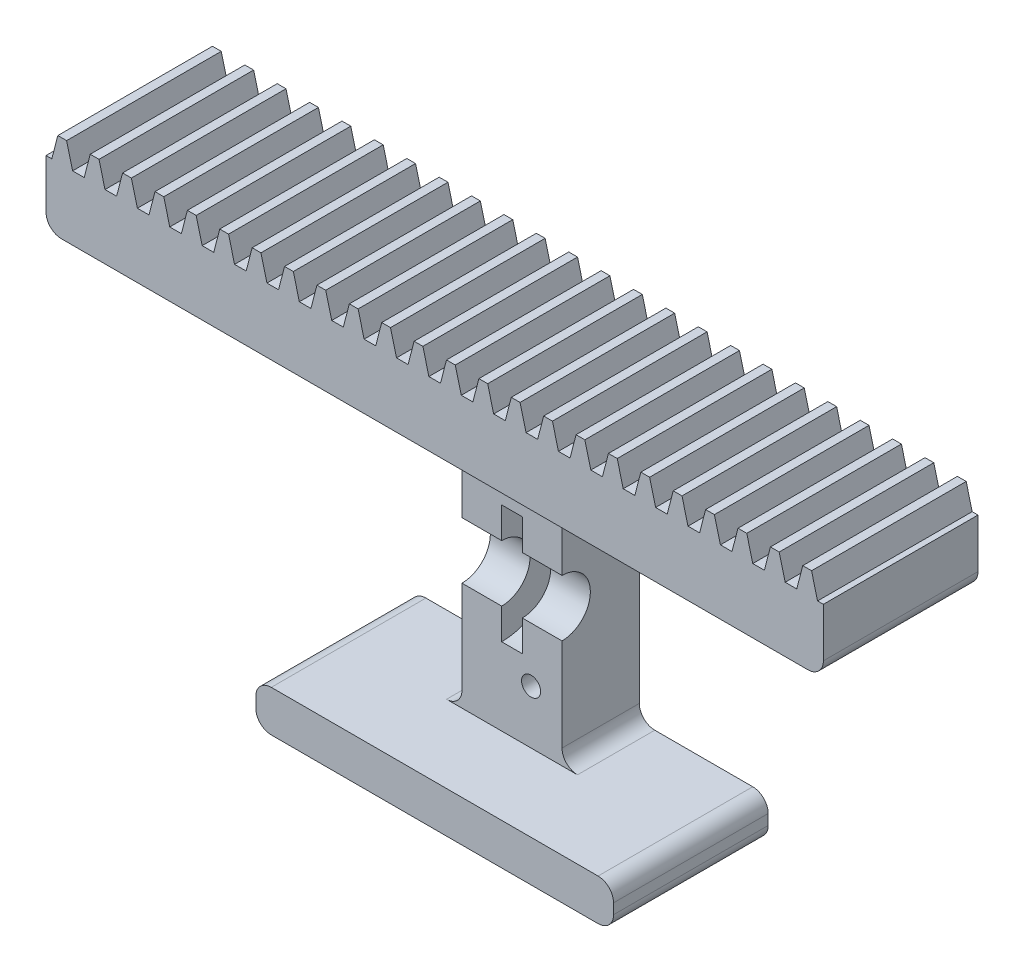
SolidWorks part; units mm, degrees
ref_plane "Plano frontal" through (0, 0, 0) normal (0, 0, 1) x (1, 0, 0)
ref_plane "Plano superior" through (0, 0, 0) normal (0, 1, 0) x (1, 0, 0)
ref_plane "Plano direito" through (0, 0, 0) normal (1, 0, 0) x (0, 0, -1)
sketch "Esboço1" plane through (0, 0, 0) normal (0, 0, 1) x (1, 0, 0)
  line L101 (-148.5074, 17) -> (-149.6712, 12.5)
  line L102 (-149.6712, 12.5) -> (-150.8, 12.5)
  line L103 (-150.8, 12.5) -> (-150.8, 0)
  line L104 (-150.8, 0) -> (0, 0)
  line L105 (0, 0) -> (0, 12.5)
  line L106 (0, 12.5) -> (-1.1253, 12.5)
  line L107 (-1.1253, 12.5) -> (-2.289, 17)
  line L108 (-2.289, 17) -> (-3.9942, 17)
  line L109 (-3.9942, 17) -> (-5.1579, 12.5)
  line L110 (-5.1579, 12.5) -> (-7.4084, 12.5)
  line L111 (-7.4084, 12.5) -> (-8.5722, 17)
  line L112 (-8.5722, 17) -> (-10.2773, 17)
  line L113 (-10.2773, 17) -> (-11.4411, 12.5)
  line L114 (-11.4411, 12.5) -> (-13.6916, 12.5)
  line L115 (-13.6916, 12.5) -> (-14.8554, 17)
  line L116 (-14.8554, 17) -> (-16.5605, 17)
  line L117 (-16.5605, 17) -> (-17.7243, 12.5)
  line L118 (-17.7243, 12.5) -> (-19.9748, 12.5)
  line L119 (-19.9748, 12.5) -> (-21.1386, 17)
  line L120 (-21.1386, 17) -> (-22.8437, 17)
  line L121 (-22.8437, 17) -> (-24.0075, 12.5)
  line L122 (-24.0075, 12.5) -> (-26.258, 12.5)
  line L123 (-26.258, 12.5) -> (-27.4218, 17)
  line L124 (-27.4218, 17) -> (-29.1269, 17)
  line L125 (-29.1269, 17) -> (-30.2907, 12.5)
  line L126 (-30.2907, 12.5) -> (-32.5412, 12.5)
  line L127 (-32.5412, 12.5) -> (-33.705, 17)
  line L128 (-33.705, 17) -> (-35.4101, 17)
  line L129 (-35.4101, 17) -> (-36.5739, 12.5)
  line L130 (-36.5739, 12.5) -> (-38.8244, 12.5)
  line L131 (-38.8244, 12.5) -> (-39.9881, 17)
  line L132 (-39.9881, 17) -> (-41.6933, 17)
  line L133 (-41.6933, 17) -> (-42.857, 12.5)
  line L134 (-42.857, 12.5) -> (-45.1075, 12.5)
  line L135 (-45.1075, 12.5) -> (-46.2713, 17)
  line L136 (-46.2713, 17) -> (-47.9765, 17)
  line L137 (-47.9765, 17) -> (-49.1402, 12.5)
  line L138 (-49.1402, 12.5) -> (-51.3907, 12.5)
  line L139 (-51.3907, 12.5) -> (-52.5545, 17)
  line L140 (-52.5545, 17) -> (-54.2596, 17)
  line L141 (-54.2596, 17) -> (-55.4234, 12.5)
  line L142 (-55.4234, 12.5) -> (-57.6739, 12.5)
  line L143 (-57.6739, 12.5) -> (-58.8377, 17)
  line L144 (-58.8377, 17) -> (-60.5428, 17)
  line L145 (-60.5428, 17) -> (-61.7066, 12.5)
  line L146 (-61.7066, 12.5) -> (-63.9571, 12.5)
  line L147 (-63.9571, 12.5) -> (-65.1209, 17)
  line L148 (-65.1209, 17) -> (-66.826, 17)
  line L149 (-66.826, 17) -> (-67.9898, 12.5)
  line L150 (-67.9898, 12.5) -> (-70.2403, 12.5)
  line L151 (-70.2403, 12.5) -> (-71.4041, 17)
  line L152 (-71.4041, 17) -> (-73.1092, 17)
  line L153 (-73.1092, 17) -> (-74.273, 12.5)
  line L154 (-74.273, 12.5) -> (-76.5235, 12.5)
  line L155 (-76.5235, 12.5) -> (-77.6873, 17)
  line L156 (-77.6873, 17) -> (-79.3924, 17)
  line L157 (-79.3924, 17) -> (-80.5562, 12.5)
  line L158 (-80.5562, 12.5) -> (-82.8067, 12.5)
  line L159 (-82.8067, 12.5) -> (-83.9704, 17)
  line L160 (-83.9704, 17) -> (-85.6756, 17)
  line L161 (-85.6756, 17) -> (-86.8393, 12.5)
  line L162 (-86.8393, 12.5) -> (-89.0898, 12.5)
  line L163 (-89.0898, 12.5) -> (-90.2536, 17)
  line L164 (-90.2536, 17) -> (-91.9587, 17)
  line L165 (-91.9587, 17) -> (-93.1225, 12.5)
  line L166 (-93.1225, 12.5) -> (-95.373, 12.5)
  line L167 (-95.373, 12.5) -> (-96.5368, 17)
  line L168 (-96.5368, 17) -> (-98.2419, 17)
  line L169 (-98.2419, 17) -> (-99.4057, 12.5)
  line L170 (-99.4057, 12.5) -> (-101.6562, 12.5)
  line L171 (-101.6562, 12.5) -> (-102.82, 17)
  line L172 (-102.82, 17) -> (-104.5251, 17)
  line L173 (-104.5251, 17) -> (-105.6889, 12.5)
  line L174 (-105.6889, 12.5) -> (-107.9394, 12.5)
  line L175 (-107.9394, 12.5) -> (-109.1032, 17)
  line L176 (-109.1032, 17) -> (-110.8083, 17)
  line L177 (-110.8083, 17) -> (-111.9721, 12.5)
  line L178 (-111.9721, 12.5) -> (-114.2226, 12.5)
  line L179 (-114.2226, 12.5) -> (-115.3864, 17)
  line L180 (-115.3864, 17) -> (-117.0915, 17)
  line L181 (-117.0915, 17) -> (-118.2553, 12.5)
  line L182 (-118.2553, 12.5) -> (-120.5058, 12.5)
  line L183 (-120.5058, 12.5) -> (-121.6696, 17)
  line L184 (-121.6696, 17) -> (-123.3747, 17)
  line L185 (-123.3747, 17) -> (-124.5385, 12.5)
  line L186 (-124.5385, 12.5) -> (-126.789, 12.5)
  line L187 (-126.789, 12.5) -> (-127.9527, 17)
  line L188 (-127.9527, 17) -> (-129.6579, 17)
  line L189 (-129.6579, 17) -> (-130.8216, 12.5)
  line L190 (-130.8216, 12.5) -> (-133.0721, 12.5)
  line L191 (-133.0721, 12.5) -> (-134.2359, 17)
  line L192 (-134.2359, 17) -> (-135.941, 17)
  line L193 (-135.941, 17) -> (-137.1048, 12.5)
  line L194 (-137.1048, 12.5) -> (-139.3553, 12.5)
  line L195 (-139.3553, 12.5) -> (-140.5191, 17)
  line L196 (-140.5191, 17) -> (-142.2242, 17)
  line L197 (-142.2242, 17) -> (-143.388, 12.5)
  line L198 (-143.388, 12.5) -> (-145.6385, 12.5)
  line L199 (-145.6385, 12.5) -> (-146.8023, 17)
  line L200 (-146.8023, 17) -> (-148.5074, 17)
  line L201 (-148.5074, 17) -> (-149.6712, 12.5)
  line L202 (-149.6712, 12.5) -> (-150.8, 12.5)
  line L203 (-150.8, 12.5) -> (-150.8, 0)
  line L204 (-150.8, 0) -> (0, 0)
  line L205 (0, 0) -> (0, 12.5)
  line L206 (0, 12.5) -> (-1.1253, 12.5)
  line L207 (-1.1253, 12.5) -> (-2.289, 17)
  line L208 (-2.289, 17) -> (-3.9942, 17)
  line L209 (-3.9942, 17) -> (-5.1579, 12.5)
  line L210 (-5.1579, 12.5) -> (-7.4084, 12.5)
  line L211 (-7.4084, 12.5) -> (-8.5722, 17)
  line L212 (-8.5722, 17) -> (-10.2773, 17)
  line L213 (-10.2773, 17) -> (-11.4411, 12.5)
  line L214 (-11.4411, 12.5) -> (-13.6916, 12.5)
  line L215 (-13.6916, 12.5) -> (-14.8554, 17)
  line L216 (-14.8554, 17) -> (-16.5605, 17)
  line L217 (-16.5605, 17) -> (-17.7243, 12.5)
  line L218 (-17.7243, 12.5) -> (-19.9748, 12.5)
  line L219 (-19.9748, 12.5) -> (-21.1386, 17)
  line L220 (-21.1386, 17) -> (-22.8437, 17)
  line L221 (-22.8437, 17) -> (-24.0075, 12.5)
  line L222 (-24.0075, 12.5) -> (-26.258, 12.5)
  line L223 (-26.258, 12.5) -> (-27.4218, 17)
  line L224 (-27.4218, 17) -> (-29.1269, 17)
  line L225 (-29.1269, 17) -> (-30.2907, 12.5)
  line L226 (-30.2907, 12.5) -> (-32.5412, 12.5)
  line L227 (-32.5412, 12.5) -> (-33.705, 17)
  line L228 (-33.705, 17) -> (-35.4101, 17)
  line L229 (-35.4101, 17) -> (-36.5739, 12.5)
  line L230 (-36.5739, 12.5) -> (-38.8244, 12.5)
  line L231 (-38.8244, 12.5) -> (-39.9881, 17)
  line L232 (-39.9881, 17) -> (-41.6933, 17)
  line L233 (-41.6933, 17) -> (-42.857, 12.5)
  line L234 (-42.857, 12.5) -> (-45.1075, 12.5)
  line L235 (-45.1075, 12.5) -> (-46.2713, 17)
  line L236 (-46.2713, 17) -> (-47.9765, 17)
  line L237 (-47.9765, 17) -> (-49.1402, 12.5)
  line L238 (-49.1402, 12.5) -> (-51.3907, 12.5)
  line L239 (-51.3907, 12.5) -> (-52.5545, 17)
  line L240 (-52.5545, 17) -> (-54.2596, 17)
  line L241 (-54.2596, 17) -> (-55.4234, 12.5)
  line L242 (-55.4234, 12.5) -> (-57.6739, 12.5)
  line L243 (-57.6739, 12.5) -> (-58.8377, 17)
  line L244 (-58.8377, 17) -> (-60.5428, 17)
  line L245 (-60.5428, 17) -> (-61.7066, 12.5)
  line L246 (-61.7066, 12.5) -> (-63.9571, 12.5)
  line L247 (-63.9571, 12.5) -> (-65.1209, 17)
  line L248 (-65.1209, 17) -> (-66.826, 17)
  line L249 (-66.826, 17) -> (-67.9898, 12.5)
  line L250 (-67.9898, 12.5) -> (-70.2403, 12.5)
  line L251 (-70.2403, 12.5) -> (-71.4041, 17)
  line L252 (-71.4041, 17) -> (-73.1092, 17)
  line L253 (-73.1092, 17) -> (-74.273, 12.5)
  line L254 (-74.273, 12.5) -> (-76.5235, 12.5)
  line L255 (-76.5235, 12.5) -> (-77.6873, 17)
  line L256 (-77.6873, 17) -> (-79.3924, 17)
  line L257 (-79.3924, 17) -> (-80.5562, 12.5)
  line L258 (-80.5562, 12.5) -> (-82.8067, 12.5)
  line L259 (-82.8067, 12.5) -> (-83.9704, 17)
  line L260 (-83.9704, 17) -> (-85.6756, 17)
  line L261 (-85.6756, 17) -> (-86.8393, 12.5)
  line L262 (-86.8393, 12.5) -> (-89.0898, 12.5)
  line L263 (-89.0898, 12.5) -> (-90.2536, 17)
  line L264 (-90.2536, 17) -> (-91.9587, 17)
  line L265 (-91.9587, 17) -> (-93.1225, 12.5)
  line L266 (-93.1225, 12.5) -> (-95.373, 12.5)
  line L267 (-95.373, 12.5) -> (-96.5368, 17)
  line L268 (-96.5368, 17) -> (-98.2419, 17)
  line L269 (-98.2419, 17) -> (-99.4057, 12.5)
  line L270 (-99.4057, 12.5) -> (-101.6562, 12.5)
  line L271 (-101.6562, 12.5) -> (-102.82, 17)
  line L272 (-102.82, 17) -> (-104.5251, 17)
  line L273 (-104.5251, 17) -> (-105.6889, 12.5)
  line L274 (-105.6889, 12.5) -> (-107.9394, 12.5)
  line L275 (-107.9394, 12.5) -> (-109.1032, 17)
  line L276 (-109.1032, 17) -> (-110.8083, 17)
  line L277 (-110.8083, 17) -> (-111.9721, 12.5)
  line L278 (-111.9721, 12.5) -> (-114.2226, 12.5)
  line L279 (-114.2226, 12.5) -> (-115.3864, 17)
  line L280 (-115.3864, 17) -> (-117.0915, 17)
  line L281 (-117.0915, 17) -> (-118.2553, 12.5)
  line L282 (-118.2553, 12.5) -> (-120.5058, 12.5)
  line L283 (-120.5058, 12.5) -> (-121.6696, 17)
  line L284 (-121.6696, 17) -> (-123.3747, 17)
  line L285 (-123.3747, 17) -> (-124.5385, 12.5)
  line L286 (-124.5385, 12.5) -> (-126.789, 12.5)
  line L287 (-126.789, 12.5) -> (-127.9527, 17)
  line L288 (-127.9527, 17) -> (-129.6579, 17)
  line L289 (-129.6579, 17) -> (-130.8216, 12.5)
  line L290 (-130.8216, 12.5) -> (-133.0721, 12.5)
  line L291 (-133.0721, 12.5) -> (-134.2359, 17)
  line L292 (-134.2359, 17) -> (-135.941, 17)
  line L293 (-135.941, 17) -> (-137.1048, 12.5)
  line L294 (-137.1048, 12.5) -> (-139.3553, 12.5)
  line L295 (-139.3553, 12.5) -> (-140.5191, 17)
  line L296 (-140.5191, 17) -> (-142.2242, 17)
  line L297 (-142.2242, 17) -> (-143.388, 12.5)
  line L298 (-143.388, 12.5) -> (-145.6385, 12.5)
  line L299 (-145.6385, 12.5) -> (-146.8023, 17)
  line L300 (-146.8023, 17) -> (-148.5074, 17)
  dimension "D1" = 0
extrude "Ressalto-extrusão1" add sketch "Esboço1" against normal up to surface (30 mm away)
sketch "Esboço2" plane through (0, 0, -30) normal (0, 0, -1) x (-1, 0, 0)
  line L0 (0, 0) -> (150.8, 0) construction
  line L1 (85.1, 0) -> (65.7, 0)
  line L2 (85.1, 0) -> (85.1, -55)
  line L4 (65.7, 0) -> (65.7, -55)
  line L6 (85.1, -55) -> (110.1, -55)
  line L7 (110.1, -55) -> (110.1, -63)
  line L8 (77.1, -39.9) -> (77.1, -18.1) construction
  line L9 (73.7, -18.1) -> (73.7, -39.9) construction
  line L10 (65.7, -55) -> (40.7, -55)
  line L11 (40.7, -55) -> (40.7, -63)
  line L14 (150.8, 0) -> (0, 0) construction
  line L15 (110.1, -63) -> (40.7, -63)
  dimension "D1" = 55
  dimension "D2" = 8
  dimension "D3" = 8
  dimension "D4" = 8
  dimension "D5" = 25
  dimension "D6" = 25
extrude "Ressalto-extrusão2" add sketch "Esboço2" against normal up to surface (30 mm away) up to face at (-75.3983, 14.41, 0)
sketch "Esboço3" plane through (0, 0, 0) normal (0, 0, 1) x (1, 0, 0)
  line L0 (-85.1, -55) -> (-85.1, 0) construction
  line L1 (-85.1, -30.6) -> (-65.7, -30.6)
  line L2 (-85.1, -30.6) -> (-85.1, -27.4)
  line L3 (-85.1, -27.4) -> (-65.7, -27.4)
  line L4 (-65.7, -30.6) -> (-65.7, -27.4)
  line L5 (-65.7, 0) -> (-65.7, -55) construction
  line L6 (-77.1, -28.4) -> (-110.1, -28.4) construction
  line L7 (-110.1, -29.6) -> (-77.1, -29.6) construction
  dimension "D1" = 1
  dimension "D2" = 1
extrude "Corte-extrusão1" cut sketch "Esboço3" against normal up to vertex (23.85 mm away)
sketch "Esboço4" plane through (0, 0, 0) normal (0, 0, 1) x (1, 0, 0)
  line L0 (-77.1, -18.1) -> (-77.1, -39.9) construction
  line L1 (-78.1, -40.9) -> (-72.7, -40.9)
  line L2 (-78.1, -40.9) -> (-78.1, -17.1)
  line L3 (-78.1, -17.1) -> (-72.7, -17.1)
  line L4 (-72.7, -40.9) -> (-72.7, -17.1)
  line L5 (-73.7, -39.9) -> (-73.7, -18.1) construction
  line L6 (-75.4, -18.1) -> (-77.1, -18.1) construction
  line L7 (-77.1, -39.9) -> (-75.4, -39.9) construction
  dimension "D1" = 1
  dimension "D2" = 1
  dimension "D3" = 1
  dimension "D4" = 1
extrude "Corte-extrusão2" cut sketch "Esboço4" against normal blind 26.5
sketch "Esboço5" plane through (0, 0, 0) normal (0, 0, 1) x (1, 0, 0)
  line L1 (-85.1, -53) -> (-65.7, -53)
  line L2 (-85.1, -53) -> (-85.1, 0)
  line L3 (-85.1, 0) -> (-65.7, 0)
  line L4 (-65.7, -53) -> (-65.7, 0)
  line L5 (-65.7, 0) -> (-65.7, -27.4) construction
  line L9 (-150.8, 0) -> (-85.1, 0) construction
extrude "Corte-extrusão3" cut sketch "Esboço5" against normal up to vertex (15.6 mm away)
fillet "Filete1" radius 5 2 edges at (-85.1, 0, -22.8) (-65.7, 0, -22.8)
sketch "Esboço6" plane through (0, -63, 0) normal (0, -1, 0) x (1, 0, 0)
  line L0 (-110.1, 0) -> (-110.1, -30) construction
  line L1 (-40.7, 0) -> (-110.1, 0)
  line L2 (-40.7, 0) -> (-40.7, -15.6)
  line L3 (-40.7, -15.6) -> (-110.1, -15.6)
  line L4 (-110.1, 0) -> (-110.1, -15.6)
  line L5 (-85.1, -15.6) -> (-65.7, -15.6) construction
extrude "Corte-extrusão4" cut sketch "Esboço6" against normal up to surface (10 mm away) up to face at (-75.4, -53, -7.8)
fillet "Filete2" radius 3 8 edges at (-40.7, -63, -22.8) (-110.1, -63, -22.8) (-85.1, -55, -22.8) (-65.7, -55, -22.8) (0, 0, -15) (-150.8, 0, -15) (-110.1, -55, -22.8) (-40.7, -55, -22.8)
sketch "Esboço7" plane through (0, 0, -15.6) normal (0, 0, 1) x (1, 0, 0)
  line L0 (-110.1, -58) -> (-110.1, -60) construction
  line L1 (-107.1, -63) -> (-43.7, -63) construction
  line L2 (-40.7, -58) -> (-40.7, -60) construction
  line L3 (-43.7, -55) -> (-62.7, -55) construction
  line L4 (-88.1, -55) -> (-107.1, -55) construction
  line L5 (-110.1, -58) -> (-110.1, -60)
  line L6 (-107.1, -63) -> (-43.7, -63)
  line L7 (-40.7, -58) -> (-40.7, -60)
  line L8 (-43.7, -55) -> (-62.7, -55)
  line L9 (-88.1, -55) -> (-107.1, -55)
  line L10 (-85.1, -51.6) -> (-65.7, -51.6) construction
  line L11 (-85.1, -51.6) -> (-65.7, -51.6)
  line L12 (-85.1, -51.6) -> (-85.1, -52)
  line L13 (-65.7, -51.6) -> (-65.7, -52)
  arc A0 (-107.1, -55) -> (-110.1, -58) centre (-107.1, -58) ccw construction
  arc A1 (-110.1, -60) -> (-107.1, -63) centre (-107.1, -60) ccw construction
  arc A2 (-43.7, -63) -> (-40.7, -60) centre (-43.7, -60) ccw construction
  arc A3 (-40.7, -58) -> (-43.7, -55) centre (-43.7, -58) ccw construction
  arc A4 (-65.7, -52) -> (-62.7, -55) centre (-62.7, -52) ccw construction
  arc A5 (-88.1, -55) -> (-85.1, -52) centre (-88.1, -52) ccw construction
  arc A6 (-107.1, -55) -> (-110.1, -58) centre (-107.1, -58) ccw
  arc A7 (-110.1, -60) -> (-107.1, -63) centre (-107.1, -60) ccw
  arc A8 (-43.7, -63) -> (-40.7, -60) centre (-43.7, -60) ccw
  arc A9 (-40.7, -58) -> (-43.7, -55) centre (-43.7, -58) ccw
  arc A10 (-65.7, -52) -> (-62.7, -55) centre (-62.7, -52) ccw
  arc A11 (-88.1, -55) -> (-85.1, -52) centre (-88.1, -52) ccw
extrude "Ressalto-extrusão3" add sketch "Esboço7" along normal up to surface (15.6 mm away) up to face at (-75.3983, 14.1741, 0)
sketch "Esboço8" plane through (0, 0, -15.6) normal (0, 0, 1) x (1, 0, 0)
  line L0 (-85.1, -5) -> (-85.1, -27.4) construction
  line L1 (-60.7, 0) -> (-90.1, 0) construction
  circle A0 centre (-79.1, -8) radius 1.85 construction
  circle A1 centre (-71.7, -44.6) radius 1.85 construction
  circle A2 centre (-79.1, -8) radius 1.85
  circle A3 centre (-71.7, -44.6) radius 1.85
extrude "Corte-extrusão5" cut sketch "Esboço8" against normal through all
sketch "Esboço9" plane through (0, 0, -30) normal (0, 0, -1) x (-1, 0, 0)
  line L1 (79.1, -3.8431) -> (75.5, -5.9215)
  line L2 (75.5, -5.9215) -> (75.5, -10.0785)
  line L3 (75.5, -10.0785) -> (79.1, -12.1569)
  line L4 (79.1, -12.1569) -> (82.7, -10.0785)
  line L5 (82.7, -10.0785) -> (82.7, -5.9215)
  line L6 (82.7, -5.9215) -> (79.1, -3.8431)
  line L7 (71.7, -40.4431) -> (68.1, -42.5215)
  line L8 (68.1, -42.5215) -> (68.1, -46.6785)
  line L9 (68.1, -46.6785) -> (71.7, -48.7569)
  line L10 (71.7, -48.7569) -> (75.3, -46.6785)
  line L11 (75.3, -46.6785) -> (75.3, -42.5215)
  line L12 (75.3, -42.5215) -> (71.7, -40.4431)
  circle A0 centre (79.1, -8) radius 3.6 construction
  circle A1 centre (71.7, -44.6) radius 3.6 construction
  dimension "D1" = 7.2
extrude "Corte-extrusão6" cut sketch "Esboço9" against normal blind 4
sketch "Esboço10" plane through (-65.7, 0, 0) normal (1, 0, 0) x (0, 0, -1)
  line L0 (15.6, -27.4) -> (15.6, -5) construction
  line L1 (15.6, -12.7597) -> (30, -12.7597)
  line L2 (15.6, -12.7597) -> (15.6, -41.7213)
  line L3 (15.6, -41.7213) -> (30, -41.7213)
  line L4 (30, -12.7597) -> (30, -41.7213)
  line L5 (30, -5) -> (30, -52) construction
extrude "Ressalto-extrusão4" add sketch "Esboço10" against normal up to surface (19.4 mm away) up to face at (-85.1, -33.32, -17.01)
sketch "Esboço11" plane through (0, 0, -15.6) normal (0, 0, 1) x (1, 0, 0)
  line L0 (-90.1, 0) -> (-60.7, 0)
  line L1 (-85.1, -5) -> (-85.1, -51.6)
  line L2 (-65.7, -5) -> (-65.7, -51.6)
  line L3 (-65.7, -51.6) -> (-85.1, -51.6)
  arc A1 (-90.1, 0) -> (-85.1, -5) centre (-90.1, -5) cw
  arc A2 (-65.7, -5) -> (-60.7, 0) centre (-60.7, -5) cw
  circle A3 centre (-79.1, -8) radius 1.85
  circle A4 centre (-71.7, -44.6) radius 1.85
extrude "Ressalto-extrusão5" add sketch "Esboço11" along normal up to surface (15.6 mm away) up to face at (-75.3983, 14.1741, 0)
sketch "Esboço12" plane through (0, 0, 0) normal (0, 0, 1) x (1, 0, 0)
  line L0 (-43.7, -55) -> (-62.7, -55) construction
  line L1 (-90.1, 0) -> (-54.189, 0)
  line L2 (-90.1, 0) -> (-90.1, -55)
  line L3 (-90.1, -55) -> (-54.189, -55)
  line L4 (-54.189, 0) -> (-54.189, -55)
extrude "Corte-extrusão7" cut sketch "Esboço12" against normal blind 15
ref_plane "Plano1" through (-75.4, 0, 0) normal (1, 0, 0) x (0, 0, -1)
sketch "Esboço13" plane through (-75.4, 0, 0) normal (1, 0, 0) x (0, 0, -1)
  line L0 (15, -5) -> (15, -52) construction
  circle A0 centre (15, -28.5) radius 11.5
  dimension "D1" = 23
extrude "Corte-extrusão8" cut sketch "Esboço13" against normal blind 2 and the other way blind 2
sketch "Esboço14" plane through (-75.4, 0, 0) normal (1, 0, 0) x (0, 0, -1)
  line L0 (15, -5) -> (15, -52) construction
  circle A0 centre (15, -28.5) radius 5.5
  dimension "D1" = 11
extrude "Corte-extrusão9" cut sketch "Esboço14" against normal up to next and the other way up to next
sketch "Esboço15" plane through (0, 0, -30) normal (0, 0, -1) x (-1, 0, 0)
  line L0 (69.486, -41.7213) -> (71.7, -40.4431)
  line L1 (71.7, -40.4431) -> (73.914, -41.7213)
  line L2 (69.486, -41.7213) -> (68.1, -42.5215) construction
  line L3 (75.3, -42.5215) -> (73.914, -41.7213) construction
  line L4 (69.486, -41.7213) -> (73.914, -41.7213)
extrude "Corte-extrusão10" cut sketch "Esboço15" against normal up to surface (4 mm away) up to face at (-71.7, -44.3714, -26)
